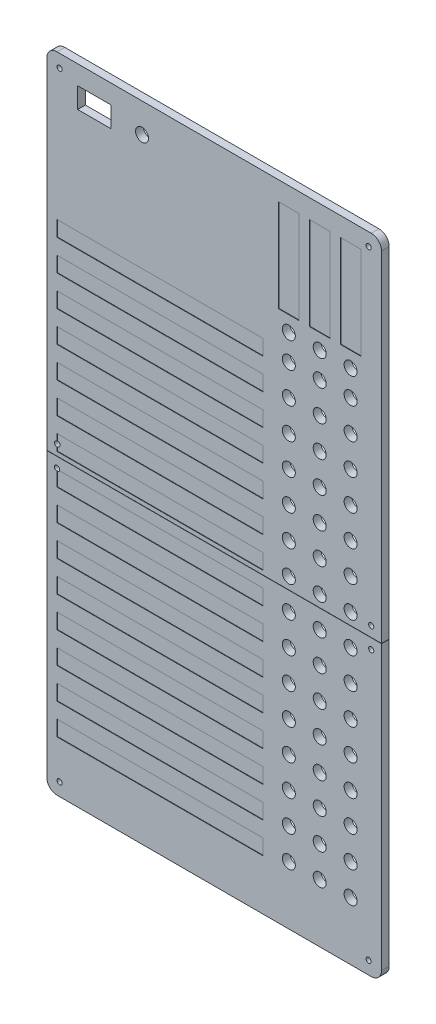
SolidWorks part; units mm, degrees
ref_plane "Ebene vorne" through (0, 0, 0) normal (0, 0, 1) x (1, 0, 0)
ref_plane "Ebene oben" through (0, 0, 0) normal (0, 1, 0) x (1, 0, 0)
ref_plane "Ebene rechts" through (0, 0, 0) normal (1, 0, 0) x (0, 0, -1)
sketch "Skizze1" plane through (0, 0, 0) normal (0, 0, 1) x (1, 0, 0)
  line L1 (0, 0) -> (130, 0)
  line L2 (0, 0) -> (0, 250)
  line L3 (0, 250) -> (130, 250)
  line L4 (130, 0) -> (130, 250)
  dimension "D1" = 250
  dimension "D2" = 130
extrude "Aufsatz-Linear austragen1" add sketch "Skizze1" along normal blind 3
fillet "Verrundung1" radius 4 1 edges at (130, 0, 1.5)
fillet "Verrundung2" radius 4 1 edges at (130, 250, 1.5)
fillet "Verrundung3" radius 4 1 edges at (0, 250, 1.5)
fillet "Verrundung4" radius 4 1 edges at (0, 0, 1.5)
hole_wizard "Ø2.0 (2) Durchmesser Bohrung1" positions "Skizze4" profile "Skizze5" hole size "Ø2.0" standard "DIN"
sketch "Skizze4" plane through (0, 0, 3) normal (0, 0, 1) x (1, 0, 0)
  line L0 (0, 246) -> (0, 4) construction
  line L1 (126, 250) -> (4, 250) construction
  line L3 (130, 4) -> (130, 246) construction
  line L4 (4, 0) -> (126, 0) construction
  point P0 (5, 5)
  point P2 (125, 5)
  point P4 (125, 245)
  point P6 (5, 245)
  dimension "D1" = 5
  dimension "D2" = 5
  dimension "D3" = 5
  dimension "D4" = 5
  dimension "D5" = 5
  dimension "D6" = 5
  dimension "D7" = 5
  dimension "D8" = 5
sketch "Skizze5" plane through (5, 5, 3) normal (1, 0, 0) x (0, -1, 0)
  line L0 (0, 0) -> (0, 3.6009)
  line L1 (0, 3.6009) -> (1, 3)
  line L2 (1, 3) -> (1, 0)
  line L5 (1, 0) -> (0, 0)
  line L10 (0, 3.6009) -> (-1, 3) construction
  line L11 (0, -6.35) -> (0, 107.95) construction
  dimension "Bohrerdurchmesser" = 2
  dimension "Bohrungstiefe" = 3
  dimension "Spitzenwinkel" = 118
sketch "Skizze6" plane through (0, 0, 3) normal (0, 0, 1) x (1, 0, 0)
  line L0 (130, 4) -> (130, 246) construction
  line L1 (90, 242.619) -> (98, 242.619)
  line L2 (90, 242.619) -> (90, 206.619)
  line L3 (90, 206.619) -> (98, 206.619)
  line L4 (98, 242.619) -> (98, 206.619)
  line L5 (102, 242.619) -> (110, 242.619)
  line L6 (102, 242.619) -> (102, 206.619)
  line L7 (102, 206.619) -> (110, 206.619)
  line L8 (110, 242.619) -> (110, 206.619)
  line L9 (114, 242.619) -> (122, 242.619)
  line L10 (114, 242.619) -> (114, 206.619)
  line L11 (114, 206.619) -> (122, 206.619)
  line L12 (122, 242.619) -> (122, 206.619)
  dimension "D1" = 8
  dimension "D2" = 8
  dimension "D3" = 8
  dimension "D4" = 4
  dimension "D5" = 4
  dimension "D6" = 8
  dimension "D7" = 36
  dimension "D8" = 36
  dimension "D9" = 36
extrude "Schnitt-Linear austragen1" cut sketch "Skizze6" against normal blind 0.2
hole_wizard "Ø5.05 (5.05) Durchmesser Bohrung1" positions "Skizze7" profile "Skizze8" hole size "Ø5.05" standard "DIN"
sketch "Skizze7" plane through (0, 0, 3) normal (0, 0, 1) x (1, 0, 0)
  line L1 (90, 206.619) -> (98, 206.619) construction
  point P8 (94, 190.619)
  point P20 (106, 190.619)
  point P21 (118, 190.619)
  point P22 (106, 178.619)
  point P23 (118, 178.619)
  point P24 (106, 166.619)
  point P25 (118, 166.619)
  point P26 (106, 154.619)
  point P27 (118, 154.619)
  point P28 (106, 142.619)
  point P29 (118, 142.619)
  point P30 (106, 130.619)
  point P31 (118, 130.619)
  point P32 (106, 118.619)
  point P33 (118, 118.619)
  point P34 (106, 106.619)
  point P35 (118, 106.619)
  point P36 (106, 94.619)
  point P37 (118, 94.619)
  point P38 (106, 82.619)
  point P39 (118, 82.619)
  point P40 (106, 70.619)
  point P41 (118, 70.619)
  point P42 (106, 58.619)
  point P43 (118, 58.619)
  point P44 (106, 46.619)
  point P45 (118, 46.619)
  point P46 (106, 34.619)
  point P47 (118, 34.619)
  point P48 (106, 22.619)
  point P49 (118, 22.619)
  point P50 (94, 178.619)
  point P51 (94, 166.619)
  point P52 (94, 154.619)
  point P53 (94, 142.619)
  point P54 (94, 130.619)
  point P55 (94, 118.619)
  point P56 (94, 106.619)
  point P57 (94, 94.619)
  point P58 (94, 82.619)
  point P59 (94, 70.619)
  point P60 (94, 58.619)
  point P61 (94, 46.619)
  point P62 (94, 34.619)
  point P63 (94, 22.619)
  dimension "D1" = 16
  dimension "D2" = 3
  dimension "D3" = 15
sketch "Skizze8" plane through (94, 190.619, 3) normal (1, 0, 0) x (0, -1, 0)
  line L0 (0, 0) -> (0, 4.5172)
  line L1 (0, 4.5172) -> (2.525, 3)
  line L2 (2.525, 3) -> (2.525, 0)
  line L5 (2.525, 0) -> (0, 0)
  line L10 (0, 4.5172) -> (-2.525, 3) construction
  line L11 (0, -6.35) -> (0, 107.95) construction
  dimension "Bohrerdurchmesser" = 5.05
  dimension "Bohrungstiefe" = 3
  dimension "Spitzenwinkel" = 118
sketch "Skizze13" plane through (0, 0, 3) normal (0, 0, 1) x (1, 0, 0)
  line L0 (0, 114) -> (130, 114)
  line L1 (0, 246) -> (0, 4) construction
  line L2 (130, 4) -> (130, 246) construction
  line L3 (4, 0) -> (126, 0) construction
  dimension "D1" = 114
extrude "Schnitt-Linear-Austragen-Dünn1" cut sketch "Skizze13" against normal blind 3 and the other way through all thin thin type mid plane wall 0.1
hole_wizard "Ø5.05 (5.05) Durchmesser Bohrung3" positions "Skizze14" profile "Skizze15" hole size "Ø5.05" standard "DIN"
sketch "Skizze14" plane through (0, 0, 3) normal (0, 0, 1) x (1, 0, 0)
  line L0 (114, 206.619) -> (122, 206.619) construction
  line L1 (102, 206.619) -> (110, 206.619) construction
  line L2 (90, 206.619) -> (98, 206.619) construction
  point P0 (94, 200.619)
  point P2 (106, 200.619)
  point P4 (118, 200.619)
  point P10 (118, 206.619)
  dimension "D1" = 6
  dimension "D2" = 6
  dimension "D3" = 6
sketch "Skizze15" plane through (94, 200.619, 3) normal (1, 0, 0) x (0, -1, 0)
  line L0 (0, 0) -> (0, 4.5172)
  line L1 (0, 4.5172) -> (2.525, 3)
  line L2 (2.525, 3) -> (2.525, 0)
  line L5 (2.525, 0) -> (0, 0)
  line L10 (0, 4.5172) -> (-2.525, 3) construction
  line L11 (0, -6.35) -> (0, 107.95) construction
  dimension "Bohrerdurchmesser" = 5.05
  dimension "Bohrungstiefe" = 3
  dimension "Spitzenwinkel" = 118
hole_wizard "Ø2.0 (2) Durchmesser Bohrung2" positions "Skizze16" profile "Skizze17" hole size "Ø2.0" standard "DIN"
sketch "Skizze16" plane through (0, 0, 3) normal (0, 0, 1) x (1, 0, 0)
  line L0 (130, 114.05) -> (130, 246) construction
  line L1 (0, 114.05) -> (130, 114.05) construction
  line L2 (130, 4) -> (130, 113.95) construction
  line L4 (0, 246) -> (0, 114.05) construction
  line L5 (0, 113.95) -> (130, 113.95) construction
  line L6 (0, 246) -> (0, 114.05) construction
  point P0 (126, 118.05)
  point P2 (4, 118.05)
  point P4 (4, 109.95)
  point P6 (126, 109.95)
  point P35 (4, 118.05)
  dimension "D1" = 4
  dimension "D2" = 4
  dimension "D3" = 4
  dimension "D4" = 4
  dimension "D5" = 4
  dimension "D6" = 4
  dimension "D7" = 4
  dimension "D8" = 4
sketch "Skizze17" plane through (126, 118.05, 3) normal (1, 0, 0) x (0, -1, 0)
  line L0 (0, 0) -> (0, 3.6009)
  line L1 (0, 3.6009) -> (1, 3)
  line L2 (1, 3) -> (1, 0)
  line L5 (1, 0) -> (0, 0)
  line L10 (0, 3.6009) -> (-1, 3) construction
  line L11 (0, -6.35) -> (0, 107.95) construction
  dimension "Bohrerdurchmesser" = 2
  dimension "Bohrungstiefe" = 3
  dimension "Spitzenwinkel" = 118
sketch "Skizze19" plane through (0, 0, 3) normal (0, 0, 1) x (1, 0, 0)
  line L0 (91.475, 190.619) -> (4.1149, 190.619) construction
  line L5 (3.902, 181.619) -> (83.902, 181.619)
  line L6 (3.902, 187.619) -> (83.902, 187.619)
  line L7 (3.902, 187.619) -> (3.902, 193.619)
  line L8 (3.902, 193.619) -> (83.902, 193.619)
  line L9 (83.902, 187.619) -> (83.902, 193.619)
  line L10 (3.902, 187.619) -> (83.902, 193.619) construction
  line L11 (3.902, 193.619) -> (83.902, 187.619) construction
  line L12 (3.902, 175.619) -> (83.902, 175.619)
  line L13 (3.902, 175.619) -> (3.902, 181.619)
  line L14 (83.902, 175.619) -> (83.902, 181.619)
  line L15 (3.902, 169.619) -> (83.902, 169.619)
  line L16 (3.902, 163.619) -> (83.902, 163.619)
  line L17 (3.902, 163.619) -> (3.902, 169.619)
  line L18 (83.902, 163.619) -> (83.902, 169.619)
  line L19 (3.902, 157.619) -> (83.902, 157.619)
  line L20 (3.902, 151.619) -> (83.902, 151.619)
  line L21 (3.902, 151.619) -> (3.902, 157.619)
  line L22 (83.902, 151.619) -> (83.902, 157.619)
  line L23 (3.902, 145.619) -> (83.902, 145.619)
  line L24 (3.902, 139.619) -> (83.902, 139.619)
  line L25 (3.902, 139.619) -> (3.902, 145.619)
  line L26 (83.902, 139.619) -> (83.902, 145.619)
  line L27 (3.902, 133.619) -> (83.902, 133.619)
  line L28 (3.902, 127.619) -> (83.902, 127.619)
  line L29 (3.902, 127.619) -> (3.902, 133.619)
  line L30 (83.902, 127.619) -> (83.902, 133.619)
  line L31 (3.902, 121.619) -> (83.902, 121.619)
  line L32 (3.902, 115.619) -> (83.902, 115.619)
  line L33 (3.902, 115.619) -> (3.902, 121.619)
  line L34 (83.902, 115.619) -> (83.902, 121.619)
  line L35 (3.902, 109.619) -> (83.902, 109.619)
  line L36 (3.902, 103.619) -> (83.902, 103.619)
  line L37 (3.902, 103.619) -> (3.902, 109.619)
  line L38 (83.902, 103.619) -> (83.902, 109.619)
  line L39 (3.902, 97.619) -> (83.902, 97.619)
  line L40 (3.902, 91.619) -> (83.902, 91.619)
  line L41 (3.902, 91.619) -> (3.902, 97.619)
  line L42 (83.902, 91.619) -> (83.902, 97.619)
  line L43 (3.902, 85.619) -> (83.902, 85.619)
  line L44 (3.902, 79.619) -> (83.902, 79.619)
  line L45 (3.902, 79.619) -> (3.902, 85.619)
  line L46 (83.902, 79.619) -> (83.902, 85.619)
  line L47 (3.902, 73.619) -> (83.902, 73.619)
  line L48 (3.902, 67.619) -> (83.902, 67.619)
  line L49 (3.902, 67.619) -> (3.902, 73.619)
  line L50 (83.902, 67.619) -> (83.902, 73.619)
  line L51 (3.902, 61.619) -> (83.902, 61.619)
  line L52 (3.902, 55.619) -> (83.902, 55.619)
  line L53 (3.902, 55.619) -> (3.902, 61.619)
  line L54 (83.902, 55.619) -> (83.902, 61.619)
  line L55 (3.902, 49.619) -> (83.902, 49.619)
  line L56 (3.902, 43.619) -> (83.902, 43.619)
  line L57 (3.902, 43.619) -> (3.902, 49.619)
  line L58 (83.902, 43.619) -> (83.902, 49.619)
  line L59 (3.902, 37.619) -> (83.902, 37.619)
  line L60 (3.902, 31.619) -> (83.902, 31.619)
  line L61 (3.902, 31.619) -> (3.902, 37.619)
  line L62 (83.902, 31.619) -> (83.902, 37.619)
  line L63 (3.902, 25.619) -> (83.902, 25.619)
  line L64 (3.902, 19.619) -> (83.902, 19.619)
  line L65 (3.902, 19.619) -> (3.902, 25.619)
  line L66 (83.902, 19.619) -> (83.902, 25.619)
  circle A0 centre (94, 190.619) radius 2.525 construction
  point P0 (43.902, 190.619)
  point P13 (43.902, 178.619)
  point P18 (43.902, 166.619)
  point P23 (43.902, 154.619)
  point P28 (43.902, 142.619)
  point P33 (43.902, 130.619)
  point P38 (43.902, 118.619)
  point P43 (43.902, 106.619)
  point P48 (43.902, 94.619)
  point P53 (43.902, 82.619)
  point P58 (43.902, 70.619)
  point P63 (43.902, 58.619)
  point P68 (43.902, 46.619)
  point P73 (43.902, 34.619)
  point P78 (43.902, 22.619)
  dimension "D1" = 6
  dimension "D2" = 80
  dimension "D3" = 15
extrude "Schnitt-Linear austragen2" cut sketch "Skizze19" against normal blind 0.2
sketch "Skizze20" plane through (0, 0, 3) normal (0, 0, 1) x (1, 0, 0)
  line L0 (90, 242.619) -> (77, 242.619) construction
  line L1 (12, 242.619) -> (25, 242.619)
  line L2 (12, 242.619) -> (12, 234.619)
  line L3 (12, 234.619) -> (25, 234.619)
  line L4 (25, 242.619) -> (25, 234.619)
  line L8 (0, 246) -> (0, 114.05) construction
  dimension "D1" = 13
  dimension "D2" = 8
  dimension "D3" = 12
extrude "Schnitt-Linear austragen3" cut sketch "Skizze20" against normal blind 30
hole_wizard "Ø5.05 (5.05) Durchmesser Bohrung4" positions "Skizze21" profile "Skizze22" hole size "Ø5.05" standard "DIN"
sketch "Skizze21" plane through (0, 0, 3) normal (0, 0, 1) x (1, 0, 0)
  line L0 (25, 234.619) -> (25, 242.619) construction
  point P0 (37, 238.619)
  dimension "D1" = 12
sketch "Skizze22" plane through (37, 238.619, 3) normal (1, 0, 0) x (0, -1, 0)
  line L0 (0, 0) -> (0, 4.5172)
  line L1 (0, 4.5172) -> (2.525, 3)
  line L2 (2.525, 3) -> (2.525, 0)
  line L5 (2.525, 0) -> (0, 0)
  line L10 (0, 4.5172) -> (-2.525, 3) construction
  line L11 (0, -6.35) -> (0, 107.95) construction
  dimension "Bohrerdurchmesser" = 5.05
  dimension "Bohrungstiefe" = 3
  dimension "Spitzenwinkel" = 118
